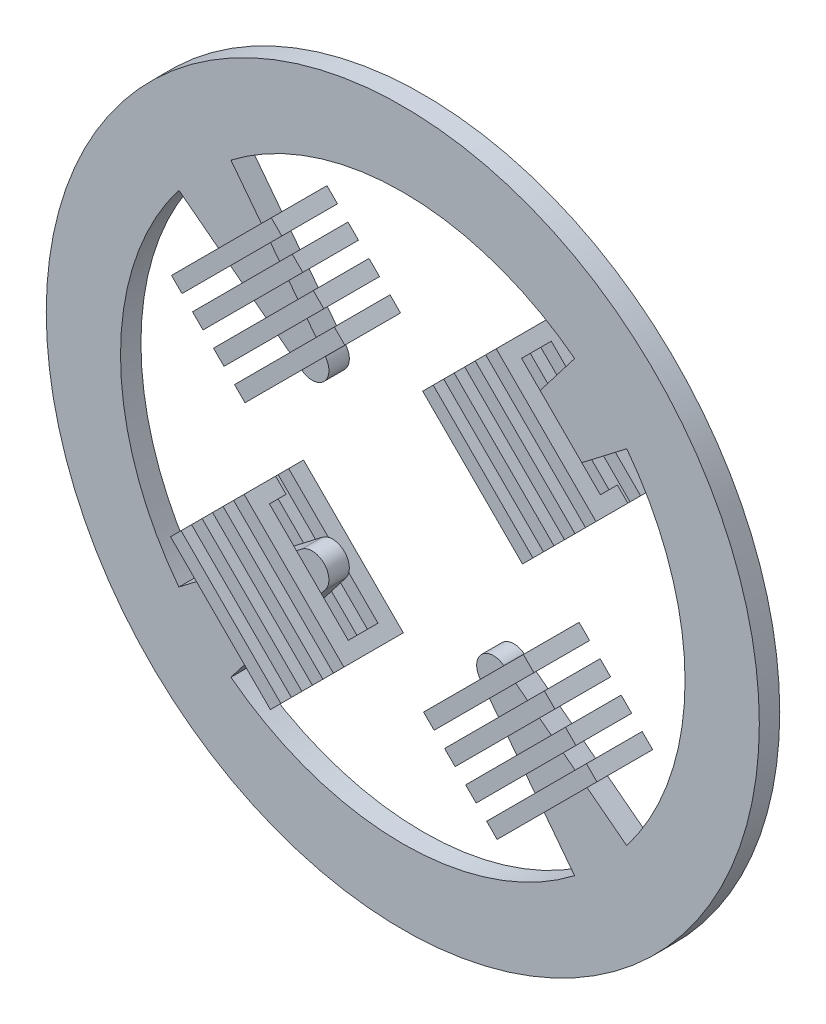
SolidWorks part; units mm, degrees
other "標示1"
sketch "草圖65"
ref_plane "前基準面" through (0, 0, 0) normal (0, 0, 1) x (1, 0, 0)
ref_plane "上基準面" through (0, 0, 0) normal (0, 1, 0) x (1, 0, 0)
ref_plane "右基準面" through (0, 0, 0) normal (1, 0, 0) x (0, 0, -1)
sketch "草圖1" plane through (0, 0, 0) normal (0, 0, 1) x (1, 0, 0)
  circle A0 centre (0, 0) radius 0.96
  circle A1 centre (0, 0) radius 0.76
extrude "填料-伸長1" add sketch "草圖1" along normal blind 0.055
sketch "草圖2" plane through (0, 0, 0.055) normal (0, 0, 1) x (1, 0, 0)
  line L0 (0, 0) -> (0, 1.565) construction
  line L1 (0, 0) -> (-1.8584, 0) construction
  line L2 (-0.0447, 0.3392) -> (-0.0992, 0.7535)
  line L3 (0.0447, 0.3392) -> (0.0992, 0.7535)
  line L4 (0.2714, 0.2082) -> (0.6029, 0.4627)
  line L5 (0.2082, 0.2714) -> (0.4627, 0.6029)
  line L6 (0.2082, -0.2714) -> (0.4627, -0.6029)
  line L7 (0.2714, -0.2082) -> (0.6029, -0.4627)
  line L8 (-0.2714, -0.2082) -> (-0.6029, -0.4627)
  line L9 (-0.2082, -0.2714) -> (-0.4627, -0.6029)
  line L10 (-0.2082, 0.2714) -> (-0.4627, 0.6029)
  line L11 (-0.2714, 0.2082) -> (-0.6029, 0.4627)
  circle A0 centre (0, 0) radius 0.3
  circle A1 centre (0, 0) radius 0.76 construction
  arc A3 (-0.0447, 0.3392) -> (0.0447, 0.3392) centre (0, 0.345) ccw
  arc A4 (0.0992, 0.7535) -> (-0.0992, 0.7535) centre (0, 0) ccw
  arc A5 (-0.76, 0) -> (0.76, 0) centre (0, 0) ccw
  arc A6 (0.6029, 0.4627) -> (0.4627, 0.6029) centre (0, 0) ccw
  arc A7 (0.2082, 0.2714) -> (0.2714, 0.2082) centre (0.244, 0.244) ccw
  arc A8 (0.4627, -0.6029) -> (0.6029, -0.4627) centre (0, 0) ccw
  arc A9 (0.2714, -0.2082) -> (0.2082, -0.2714) centre (0.244, -0.244) ccw
  arc A10 (-0.6029, -0.4627) -> (-0.4627, -0.6029) centre (0, 0) ccw
  arc A11 (-0.2082, -0.2714) -> (-0.2714, -0.2082) centre (-0.244, -0.244) ccw
  arc A12 (-0.4627, 0.6029) -> (-0.6029, 0.4627) centre (0, 0) ccw
  arc A13 (-0.2714, 0.2082) -> (-0.2082, 0.2714) centre (-0.244, 0.244) ccw
  point P23 (0, 0)
  point P34 (0, 0)
  point P41 (0, 0)
  circle M4 centre (0, 0) radius 0.76
  dimension "D1" = 7.5
  dimension "D3" = 2
  dimension "D4" = 4
  dimension "D2" = 7.5
extrude "填料-伸長2" add sketch "草圖2" against normal blind 0.055 contours L11 A13 L10 M4 | L5 A7 L4 M4 | L7 A9 L6 M4 | A11 L8 L9 M4
sketch "草圖7" plane through (0, 0, 0.055) normal (0, 0, 1) x (1, 0, 0)
  line L0 (0.2121, 0.2121) -> (0.2404, 0.2404) construction
  line L1 (0.2404, 0.2404) -> (0.2013, 0.2795) construction
  line L2 (0.2404, 0.2404) -> (0.5894, 0.5894) construction
  line L3 (0.0244, -0.0244) -> (-0.6648, 0.6648) construction
  line L4 (0.2404, -0.2404) -> (0.3328, -0.148)
  arc A0 (0.2082, 0.2714) -> (0.2714, 0.2082) centre (0.244, 0.244) ccw construction
  arc A1 (-0.2082, -0.2714) -> (-0.2714, -0.2082) centre (-0.244, -0.244) ccw construction
  arc A2 (-0.2714, 0.2082) -> (-0.2082, 0.2714) centre (-0.244, 0.244) ccw construction
  arc A3 (0.2714, -0.2082) -> (0.2082, -0.2714) centre (0.244, -0.244) ccw construction
  point P5 (0.297, 0.297)
  point P7 (-0.2121, -0.2121)
  point P8 (0.3536, 0.3536)
  point P9 (0.4101, 0.4101)
  point P12 (-0.2404, -0.2404)
  point P16 (-0.297, -0.297)
  point P17 (-0.3536, -0.3536)
  point P18 (-0.4101, -0.4101)
  point P20 (0.2404, -0.2404)
  point P23 (-0.2404, 0.2404)
  point P24 (-0.2121, 0.2121)
  point P25 (0.2121, -0.2121)
  point P29 (0.297, -0.297)
  point P33 (0.3536, -0.3536)
  point P34 (0.4101, -0.4101)
  point P35 (-0.297, 0.297)
  point P36 (-0.3536, 0.3536)
  point P37 (-0.4101, 0.4101)
  point P40 (0.4667, -0.4667)
  point P41 (0.5233, -0.5233)
  point P42 (0.4667, 0.4667)
  point P43 (0.5233, 0.5233)
  point P44 (-0.4667, 0.4667)
  point P45 (-0.5233, 0.5233)
  point P46 (-0.4667, -0.4667)
  point P47 (-0.5233, -0.5233)
  point P48 (0, 0)
  dimension "D1" = 0.08
  dimension "D2" = 0.08
  dimension "D3" = 0.08
  dimension "D4" = 0.04
  dimension "D5" = 0.04
  dimension "D6" = 0.08
  dimension "D7" = 0.08
  dimension "D8" = 0.08
  dimension "D9" = 0.04
  dimension "D10" = 0.04
  dimension "D11" = 0.08
  dimension "D12" = 0.08
  dimension "D13" = 0.08
  dimension "D14" = 0.08
  dimension "D15" = 0.08
  dimension "D16" = 0.08
  dimension "D17" = 0.08
  dimension "D18" = 0.08
  dimension "D19" = 0.08
  dimension "D20" = 0.08
  dimension "D21" = 0.08
  dimension "D22" = 0.08
  dimension "D23" = 0.08
  dimension "D24" = 0.08
ref_plane "平面5" through (0.2404, 0.2404, 0) normal (0.7071, 0.7071, 0) x (-0.7071, 0.7071, 0)
sketch "草圖11" plane through (0.2404, 0.2404, 0) normal (0.7071, 0.7071, 0) x (-0.7071, 0.7071, 0)
  line L0 (0, 0.055) -> (0, 0.1261) construction
  line L1 (-0.15, 0.0675) -> (0.15, 0.0675)
  line L2 (0.19, 0.1075) -> (-0.19, 0.1075)
  line L7 (-0.19, -0.0525) -> (0.19, -0.0525)
  line L17 (0.19, 0.1075) -> (0.19, -0.0525)
  line L18 (-0.19, 0.1075) -> (-0.19, -0.0525)
  line L19 (-0.15, -0.0125) -> (0.15, -0.0125)
  line L20 (-0.15, 0.0675) -> (-0.15, -0.0125)
  line L21 (0.15, 0.0675) -> (0.15, -0.0125)
  point P1 (0, 0.0275)
  point P2 (0, -0.0125)
  point P9 (0, 0.055)
  point P10 (0, -0.0525)
  point P11 (0, 0)
  point P13 (0, 0.1075)
  point P16 (0, -0.0525)
  point P19 (0, 0.0675)
  point P21 (0, 0.0675)
  point P22 (0, 0.1075)
  point P24 (0, -0.0125)
  dimension "D1" = 0.04
  dimension "D2" = 0.04
  dimension "D3" = 0.38
  dimension "D4" = 0.04
  dimension "D7" = 0.04
extrude "填料-伸長3" add sketch "草圖11" along normal blind 0.04 separate body
ref_plane "平面6" through (0.297, 0.297, 0) normal (0.7071, 0.7071, 0) x (0.7071, -0.7071, 0)
ref_plane "平面7" through (0.3536, 0.3536, 0) normal (0.7071, 0.7071, 0) x (0.7071, -0.7071, 0)
ref_plane "平面8" through (0.4101, 0.4101, 0) normal (0.7071, 0.7071, 0) x (0.7071, -0.7071, 0)
ref_plane "平面9" through (-0.2404, -0.2404, 0) normal (0.7071, 0.7071, 0) x (0.7071, -0.7071, 0)
ref_plane "平面10" through (-0.297, -0.297, 0) normal (0.7071, 0.7071, 0) x (0.7071, -0.7071, 0)
ref_plane "平面11" through (-0.3536, -0.3536, 0) normal (0.7071, 0.7071, 0) x (0.7071, -0.7071, 0)
ref_plane "平面12" through (-0.4101, -0.4101, 0) normal (0.7071, 0.7071, 0) x (0.7071, -0.7071, 0)
ref_plane "平面13" through (0.2404, -0.2404, 0) normal (0.7071, -0.7071, 0) x (0.7071, 0.7071, 0)
ref_plane "平面14" through (0.297, -0.297, 0) normal (0.7071, -0.7071, 0) x (0, 0, -1)
ref_plane "平面15" through (0.3536, -0.3536, 0) normal (0.7071, -0.7071, 0) x (0, 0, -1)
ref_plane "平面16" through (0.4101, -0.4101, 0) normal (0.7071, -0.7071, 0) x (0, 0, -1)
ref_plane "平面17" through (-0.2404, 0.2404, 0) normal (0.7071, -0.7071, 0) x (0, 0, -1)
ref_plane "平面18" through (-0.297, 0.297, 0) normal (0.7071, -0.7071, 0) x (0, 0, -1)
ref_plane "平面19" through (-0.3536, 0.3536, 0) normal (0.7071, -0.7071, 0) x (0, 0, -1)
ref_plane "平面20" through (-0.4101, 0.4101, 0) normal (0.7071, -0.7071, 0) x (0, 0, -1)
sketch "草圖60" plane through (0.2404, -0.2404, 0) normal (0.7071, -0.7071, 0) x (0.7071, 0.7071, 0)
sketch "草圖62" plane through (0.2404, -0.2404, 0) normal (0.7071, -0.7071, 0) x (0.7071, 0.7071, 0)
  line L0 (0, -0.0586) -> (0, 0.1686)
  line L2 (0.15, 0.065) -> (-0.15, 0.065)
  line L3 (-0.15, 0.065) -> (-0.15, -0.005)
  line L4 (-0.15, -0.005) -> (0.15, -0.005)
  line L5 (0.15, -0.005) -> (0.15, 0.065)
  line L6 (0.19, 0.105) -> (-0.19, 0.105)
  line L7 (-0.19, 0.105) -> (-0.19, -0.045)
  line L8 (-0.19, -0.045) -> (0.19, -0.045)
  line L9 (0.19, -0.045) -> (0.19, 0.105)
  point P0 (0, 0.065)
  point P4 (0, 0.055)
  point P5 (0, -0.005)
  point P8 (0, 0.105)
  point P11 (0, 0.065)
  point P14 (0, -0.045)
  point P18 (0, 0.105)
  dimension "D1" = 0.01
  dimension "D2" = 0.06
  dimension "D3" = 0.04
  dimension "D4" = 0.04
  dimension "D5" = 0.38
  dimension "D6" = 0.3
sketch "草圖64" plane through (0.297, -0.297, 0) normal (0.7071, -0.7071, 0) x (0, 0, -1)
  line L0 (0.045, 0.19) -> (-0.105, 0.19) construction
  line L1 (0.005, 0.15) -> (-0.065, 0.15) construction
  line L2 (0.045, -0.19) -> (0.045, 0.19) construction
  line L3 (0.005, -0.15) -> (0.005, 0.15) construction
  line L4 (-0.065, -0.15) -> (0.005, -0.15) construction
  line L5 (-0.065, 0.15) -> (-0.065, -0.15) construction
  line L6 (-0.105, -0.19) -> (0.045, -0.19) construction
  line L7 (-0.105, 0.19) -> (-0.105, -0.19) construction
  line L8 (0.045, 0.19) -> (-0.105, 0.19)
  line L9 (0.005, 0.15) -> (-0.065, 0.15)
  line L10 (0.045, -0.19) -> (0.045, 0.19)
  line L11 (0.005, -0.15) -> (0.005, 0.15)
  line L12 (-0.065, -0.15) -> (0.005, -0.15)
  line L13 (-0.065, 0.15) -> (-0.065, -0.15)
  line L14 (-0.105, -0.19) -> (0.045, -0.19)
  line L15 (-0.105, 0.19) -> (-0.105, -0.19)
sketch "草圖68" plane through (0.3536, -0.3536, 0) normal (0.7071, -0.7071, 0) x (0, 0, -1)
  line L0 (-0.105, -0.19) -> (0.045, -0.19) construction
  line L1 (-0.065, -0.15) -> (0.005, -0.15) construction
  line L2 (0.005, -0.15) -> (0.005, 0.15) construction
  line L3 (-0.065, 0.15) -> (-0.065, -0.15) construction
  line L4 (0.005, 0.15) -> (-0.065, 0.15) construction
  line L5 (0.045, -0.19) -> (0.045, 0.19) construction
  line L6 (0.045, 0.19) -> (-0.105, 0.19) construction
  line L7 (-0.105, 0.19) -> (-0.105, -0.19) construction
  line L8 (-0.105, -0.19) -> (0.045, -0.19)
  line L9 (-0.065, -0.15) -> (0.005, -0.15)
  line L10 (0.005, -0.15) -> (0.005, 0.15)
  line L11 (-0.065, 0.15) -> (-0.065, -0.15)
  line L12 (0.005, 0.15) -> (-0.065, 0.15)
  line L13 (0.045, -0.19) -> (0.045, 0.19)
  line L14 (0.045, 0.19) -> (-0.105, 0.19)
  line L15 (-0.105, 0.19) -> (-0.105, -0.19)
sketch "草圖69" plane through (0.4101, -0.4101, 0) normal (0.7071, -0.7071, 0) x (0, 0, -1)
  line L0 (0.045, -0.19) -> (0.045, 0.19) construction
  line L1 (0.045, 0.19) -> (-0.105, 0.19) construction
  line L2 (-0.105, 0.19) -> (-0.105, -0.19) construction
  line L3 (-0.105, -0.19) -> (0.045, -0.19) construction
  line L4 (-0.065, -0.15) -> (0.005, -0.15) construction
  line L5 (0.005, -0.15) -> (0.005, 0.15) construction
  line L6 (-0.065, 0.15) -> (-0.065, -0.15) construction
  line L7 (0.005, 0.15) -> (-0.065, 0.15) construction
  line L8 (0.045, -0.19) -> (0.045, 0.19)
  line L9 (0.045, 0.19) -> (-0.105, 0.19)
  line L10 (-0.105, 0.19) -> (-0.105, -0.19)
  line L11 (-0.105, -0.19) -> (0.045, -0.19)
  line L12 (-0.065, -0.15) -> (0.005, -0.15)
  line L13 (0.005, -0.15) -> (0.005, 0.15)
  line L14 (-0.065, 0.15) -> (-0.065, -0.15)
  line L15 (0.005, 0.15) -> (-0.065, 0.15)
sketch "草圖70" plane through (-0.2404, 0.2404, 0) normal (0.7071, -0.7071, 0) x (0, 0, -1)
  line L0 (-0.105, 0.19) -> (-0.105, -0.19) construction
  line L1 (-0.105, -0.19) -> (0.045, -0.19) construction
  line L2 (-0.065, -0.15) -> (0.005, -0.15) construction
  line L3 (-0.065, 0.15) -> (-0.065, -0.15) construction
  line L4 (0.005, -0.15) -> (0.005, 0.15) construction
  line L5 (0.005, 0.15) -> (-0.065, 0.15) construction
  line L6 (0.045, -0.19) -> (0.045, 0.19) construction
  line L7 (0.045, 0.19) -> (-0.105, 0.19) construction
  line L8 (-0.105, 0.19) -> (-0.105, -0.19)
  line L9 (-0.105, -0.19) -> (0.045, -0.19)
  line L10 (-0.065, -0.15) -> (0.005, -0.15)
  line L11 (-0.065, 0.15) -> (-0.065, -0.15)
  line L12 (0.005, -0.15) -> (0.005, 0.15)
  line L13 (0.005, 0.15) -> (-0.065, 0.15)
  line L14 (0.045, -0.19) -> (0.045, 0.19)
  line L15 (0.045, 0.19) -> (-0.105, 0.19)
sketch "草圖71" plane through (-0.297, 0.297, 0) normal (0.7071, -0.7071, 0) x (0, 0, -1)
  line L0 (0.045, -0.19) -> (0.045, 0.19) construction
  line L1 (-0.105, -0.19) -> (0.045, -0.19) construction
  line L2 (-0.065, -0.15) -> (0.005, -0.15) construction
  line L3 (0.005, -0.15) -> (0.005, 0.15) construction
  line L4 (-0.065, 0.15) -> (-0.065, -0.15) construction
  line L5 (0.005, 0.15) -> (-0.065, 0.15) construction
  line L6 (-0.105, 0.19) -> (-0.105, -0.19) construction
  line L7 (0.045, 0.19) -> (-0.105, 0.19) construction
  line L8 (0.045, -0.19) -> (0.045, 0.19)
  line L9 (-0.105, -0.19) -> (0.045, -0.19)
  line L10 (-0.065, -0.15) -> (0.005, -0.15)
  line L11 (0.005, -0.15) -> (0.005, 0.15)
  line L12 (-0.065, 0.15) -> (-0.065, -0.15)
  line L13 (0.005, 0.15) -> (-0.065, 0.15)
  line L14 (-0.105, 0.19) -> (-0.105, -0.19)
  line L15 (0.045, 0.19) -> (-0.105, 0.19)
sketch "草圖72" plane through (-0.3536, 0.3536, 0) normal (0.7071, -0.7071, 0) x (0, 0, -1)
  line L0 (-0.105, -0.19) -> (0.045, -0.19) construction
  line L1 (-0.105, 0.19) -> (-0.105, -0.19) construction
  line L2 (-0.065, 0.15) -> (-0.065, -0.15) construction
  line L3 (0.005, -0.15) -> (0.005, 0.15) construction
  line L4 (0.005, 0.15) -> (-0.065, 0.15) construction
  line L5 (0.045, 0.19) -> (-0.105, 0.19) construction
  line L6 (0.045, -0.19) -> (0.045, 0.19) construction
  line L7 (-0.105, -0.19) -> (0.045, -0.19)
  line L8 (-0.105, 0.19) -> (-0.105, -0.19)
  line L9 (-0.065, 0.15) -> (-0.065, -0.15)
  line L10 (0.005, -0.15) -> (0.005, 0.15)
  line L11 (0.005, 0.15) -> (-0.065, 0.15)
  line L12 (0.045, 0.19) -> (-0.105, 0.19)
  line L13 (0.045, -0.19) -> (0.045, 0.19)
  line L14 (-0.065, -0.15) -> (0.005, -0.15)
sketch "草圖73" plane through (-0.4101, 0.4101, 0) normal (0.7071, -0.7071, 0) x (0, 0, -1)
  line L0 (-0.065, -0.15) -> (0.005, -0.15) construction
  line L1 (-0.105, -0.19) -> (0.045, -0.19) construction
  line L2 (-0.105, 0.19) -> (-0.105, -0.19) construction
  line L3 (-0.065, 0.15) -> (-0.065, -0.15) construction
  line L4 (0.005, 0.15) -> (-0.065, 0.15) construction
  line L5 (0.005, -0.15) -> (0.005, 0.15) construction
  line L6 (0.045, -0.19) -> (0.045, 0.19) construction
  line L7 (0.045, 0.19) -> (-0.105, 0.19) construction
  line L8 (-0.065, -0.15) -> (0.005, -0.15)
  line L9 (-0.105, -0.19) -> (0.045, -0.19)
  line L10 (-0.105, 0.19) -> (-0.105, -0.19)
  line L11 (-0.065, 0.15) -> (-0.065, -0.15)
  line L12 (0.005, 0.15) -> (-0.065, 0.15)
  line L13 (0.005, -0.15) -> (0.005, 0.15)
  line L14 (0.045, -0.19) -> (0.045, 0.19)
  line L15 (0.045, 0.19) -> (-0.105, 0.19)
sketch "草圖74" plane through (-0.3536, 0.3536, 0) normal (0.7071, -0.7071, 0) x (0, 0, -1)
  line L0 (-0.065, -0.15) -> (0.005, -0.15) construction
  line L1 (-0.065, -0.15) -> (0.005, -0.15)
extrude "填料-伸長28" add sketch "草圖62" along normal blind 0.04 separate body contours L8 L9 L6 L0 L2 L5 L4 | L7 L8 L0 L4 L3 L2 L6
extrude "填料-伸長29" add sketch "草圖64" along normal blind 0.04 separate body
extrude "填料-伸長30" add sketch "草圖68" along normal blind 0.04 separate body
extrude "填料-伸長31" add sketch "草圖69" along normal blind 0.04 separate body
extrude "填料-伸長32" add sketch "草圖70" against normal blind 0.04 separate body
extrude "填料-伸長33" add sketch "草圖71" against normal blind 0.04 separate body
extrude "填料-伸長34" add sketch "草圖72" against normal blind 0.04 separate body
extrude "填料-伸長35" add sketch "草圖73" against normal blind 0.04 separate body
sketch "草圖76" plane through (0.297, 0.297, 0) normal (0.7071, 0.7071, 0) x (0.7071, -0.7071, 0)
  line L0 (0.19, -0.1075) -> (0.19, 0.0525) construction
  line L1 (0.15, -0.0675) -> (0.15, 0.0125) construction
  line L2 (-0.19, -0.1075) -> (0.19, -0.1075) construction
  line L3 (0.15, -0.0675) -> (-0.15, -0.0675) construction
  line L4 (-0.15, -0.0675) -> (-0.15, 0.0125) construction
  line L5 (-0.19, -0.1075) -> (-0.19, 0.0525) construction
  line L6 (0.19, 0.0525) -> (-0.19, 0.0525) construction
  line L7 (0.15, 0.0125) -> (-0.15, 0.0125) construction
  line L8 (0.19, -0.1075) -> (0.19, 0.0525)
  line L9 (0.15, -0.0675) -> (0.15, 0.0125)
  line L10 (-0.19, -0.1075) -> (0.19, -0.1075)
  line L11 (0.15, -0.0675) -> (-0.15, -0.0675)
  line L12 (-0.15, -0.0675) -> (-0.15, 0.0125)
  line L13 (-0.19, -0.1075) -> (-0.19, 0.0525)
  line L14 (0.19, 0.0525) -> (-0.19, 0.0525)
  line L15 (0.15, 0.0125) -> (-0.15, 0.0125)
sketch "草圖77" plane through (0.3536, 0.3536, 0) normal (0.7071, 0.7071, 0) x (0.7071, -0.7071, 0)
  line L0 (0.19, -0.1075) -> (0.19, 0.0525) construction
  line L1 (0.15, -0.0675) -> (0.15, 0.0125) construction
  line L2 (-0.19, -0.1075) -> (0.19, -0.1075) construction
  line L3 (0.15, -0.0675) -> (-0.15, -0.0675) construction
  line L4 (-0.15, -0.0675) -> (-0.15, 0.0125) construction
  line L5 (-0.19, -0.1075) -> (-0.19, 0.0525) construction
  line L6 (0.19, 0.0525) -> (-0.19, 0.0525) construction
  line L7 (0.15, 0.0125) -> (-0.15, 0.0125) construction
  line L8 (0.19, -0.1075) -> (0.19, 0.0525)
  line L9 (0.15, -0.0675) -> (0.15, 0.0125)
  line L10 (-0.19, -0.1075) -> (0.19, -0.1075)
  line L11 (0.15, -0.0675) -> (-0.15, -0.0675)
  line L12 (-0.15, -0.0675) -> (-0.15, 0.0125)
  line L13 (-0.19, -0.1075) -> (-0.19, 0.0525)
  line L14 (0.19, 0.0525) -> (-0.19, 0.0525)
  line L15 (0.15, 0.0125) -> (-0.15, 0.0125)
sketch "草圖78" plane through (0.4101, 0.4101, 0) normal (0.7071, 0.7071, 0) x (0.7071, -0.7071, 0)
  line L0 (0.19, -0.1075) -> (0.19, 0.0525) construction
  line L1 (-0.19, -0.1075) -> (0.19, -0.1075) construction
  line L2 (0.19, 0.0525) -> (-0.19, 0.0525) construction
  line L3 (-0.19, -0.1075) -> (-0.19, 0.0525) construction
  line L4 (0.15, -0.0675) -> (-0.15, -0.0675) construction
  line L5 (0.15, -0.0675) -> (0.15, 0.0125) construction
  line L6 (0.15, 0.0125) -> (-0.15, 0.0125) construction
  line L7 (-0.15, -0.0675) -> (-0.15, 0.0125) construction
  line L8 (0.19, -0.1075) -> (0.19, 0.0525)
  line L9 (-0.19, -0.1075) -> (0.19, -0.1075)
  line L10 (0.19, 0.0525) -> (-0.19, 0.0525)
  line L11 (-0.19, -0.1075) -> (-0.19, 0.0525)
  line L12 (0.15, -0.0675) -> (-0.15, -0.0675)
  line L13 (0.15, -0.0675) -> (0.15, 0.0125)
  line L14 (0.15, 0.0125) -> (-0.15, 0.0125)
  line L15 (-0.15, -0.0675) -> (-0.15, 0.0125)
sketch "草圖79" plane through (-0.2404, -0.2404, 0) normal (0.7071, 0.7071, 0) x (0.7071, -0.7071, 0)
  line L0 (-0.19, -0.1075) -> (0.19, -0.1075) construction
  line L1 (0.15, -0.0675) -> (-0.15, -0.0675) construction
  line L2 (-0.15, -0.0675) -> (-0.15, 0.0125) construction
  line L3 (-0.19, -0.1075) -> (-0.19, 0.0525) construction
  line L4 (0.19, -0.1075) -> (0.19, 0.0525) construction
  line L5 (0.15, -0.0675) -> (0.15, 0.0125) construction
  line L6 (0.15, 0.0125) -> (-0.15, 0.0125) construction
  line L7 (0.19, 0.0525) -> (-0.19, 0.0525) construction
  line L8 (-0.19, -0.1075) -> (0.19, -0.1075)
  line L9 (0.15, -0.0675) -> (-0.15, -0.0675)
  line L10 (-0.15, -0.0675) -> (-0.15, 0.0125)
  line L11 (-0.19, -0.1075) -> (-0.19, 0.0525)
  line L12 (0.19, -0.1075) -> (0.19, 0.0525)
  line L13 (0.15, -0.0675) -> (0.15, 0.0125)
  line L14 (0.15, 0.0125) -> (-0.15, 0.0125)
  line L15 (0.19, 0.0525) -> (-0.19, 0.0525)
sketch "草圖80" plane through (-0.297, -0.297, 0) normal (0.7071, 0.7071, 0) x (0.7071, -0.7071, 0)
  line L0 (-0.19, -0.1075) -> (0.19, -0.1075) construction
  line L1 (0.19, -0.1075) -> (0.19, 0.0525) construction
  line L2 (0.19, 0.0525) -> (-0.19, 0.0525) construction
  line L3 (-0.19, -0.1075) -> (-0.19, 0.0525) construction
  line L4 (-0.15, -0.0675) -> (-0.15, 0.0125) construction
  line L5 (0.15, -0.0675) -> (-0.15, -0.0675) construction
  line L6 (0.15, -0.0675) -> (0.15, 0.0125) construction
  line L7 (0.15, 0.0125) -> (-0.15, 0.0125) construction
  line L8 (-0.19, -0.1075) -> (0.19, -0.1075)
  line L9 (0.19, -0.1075) -> (0.19, 0.0525)
  line L10 (0.19, 0.0525) -> (-0.19, 0.0525)
  line L11 (-0.19, -0.1075) -> (-0.19, 0.0525)
  line L12 (-0.15, -0.0675) -> (-0.15, 0.0125)
  line L13 (0.15, -0.0675) -> (-0.15, -0.0675)
  line L14 (0.15, -0.0675) -> (0.15, 0.0125)
  line L15 (0.15, 0.0125) -> (-0.15, 0.0125)
sketch "草圖81" plane through (-0.3536, -0.3536, 0) normal (0.7071, 0.7071, 0) x (0.7071, -0.7071, 0)
  line L0 (-0.19, -0.1075) -> (0.19, -0.1075) construction
  line L1 (0.19, -0.1075) -> (0.19, 0.0525) construction
  line L2 (0.19, 0.0525) -> (-0.19, 0.0525) construction
  line L3 (-0.19, -0.1075) -> (-0.19, 0.0525) construction
  line L4 (-0.15, -0.0675) -> (-0.15, 0.0125) construction
  line L5 (0.15, -0.0675) -> (-0.15, -0.0675) construction
  line L6 (0.15, -0.0675) -> (0.15, 0.0125) construction
  line L7 (0.15, 0.0125) -> (-0.15, 0.0125) construction
  line L8 (-0.19, -0.1075) -> (0.19, -0.1075)
  line L9 (0.19, -0.1075) -> (0.19, 0.0525)
  line L10 (0.19, 0.0525) -> (-0.19, 0.0525)
  line L11 (-0.19, -0.1075) -> (-0.19, 0.0525)
  line L12 (-0.15, -0.0675) -> (-0.15, 0.0125)
  line L13 (0.15, -0.0675) -> (-0.15, -0.0675)
  line L14 (0.15, -0.0675) -> (0.15, 0.0125)
  line L15 (0.15, 0.0125) -> (-0.15, 0.0125)
sketch "草圖82" plane through (-0.4101, -0.4101, 0) normal (0.7071, 0.7071, 0) x (0.7071, -0.7071, 0)
  line L0 (0.19, -0.1075) -> (0.19, 0.0525) construction
  line L1 (-0.19, -0.1075) -> (0.19, -0.1075) construction
  line L2 (-0.15, -0.0675) -> (-0.15, 0.0125) construction
  line L3 (0.15, -0.0675) -> (-0.15, -0.0675) construction
  line L4 (0.15, -0.0675) -> (0.15, 0.0125) construction
  line L5 (0.15, 0.0125) -> (-0.15, 0.0125) construction
  line L6 (0.19, 0.0525) -> (-0.19, 0.0525) construction
  line L7 (-0.19, -0.1075) -> (-0.19, 0.0525) construction
  line L8 (0.19, -0.1075) -> (0.19, 0.0525)
  line L9 (-0.19, -0.1075) -> (0.19, -0.1075)
  line L10 (-0.15, -0.0675) -> (-0.15, 0.0125)
  line L11 (0.15, -0.0675) -> (-0.15, -0.0675)
  line L12 (0.15, -0.0675) -> (0.15, 0.0125)
  line L13 (0.15, 0.0125) -> (-0.15, 0.0125)
  line L14 (0.19, 0.0525) -> (-0.19, 0.0525)
  line L15 (-0.19, -0.1075) -> (-0.19, 0.0525)
extrude "填料-伸長36" add sketch "草圖76" along normal blind 0.04 separate body
extrude "填料-伸長37" add sketch "草圖77" along normal blind 0.04 separate body
extrude "填料-伸長38" add sketch "草圖78" along normal blind 0.04 separate body
extrude "填料-伸長39" add sketch "草圖79" against normal blind 0.04 separate body
extrude "填料-伸長40" add sketch "草圖80" against normal blind 0.04 separate body
extrude "填料-伸長41" add sketch "草圖81" against normal blind 0.04 separate body
extrude "填料-伸長42" add sketch "草圖82" against normal blind 0.04 separate body
sketch "草圖84" plane through (0.4384, 0.4384, 0) normal (0.7071, 0.7071, 0) x (0, 0, -1)
  line L0 (0.0125, -0.15) -> (0.0125, -0.19)
  line L1 (-0.1075, -0.19) -> (0.0525, -0.19) construction
  line L2 (0.0125, -0.15) -> (-0.0218, -0.15)
  line L3 (-0.0675, -0.15) -> (0.0125, -0.15) construction
  line L4 (-0.0218, -0.15) -> (-0.0218, -0.19)
  line L5 (-0.0218, -0.19) -> (0.0125, -0.19)
extrude "除料-伸長2" cut sketch "草圖84" against normal blind 0.5
sketch "草圖85" plane through (-0.4384, -0.4384, 0) normal (-0.7071, -0.7071, 0) x (0, 0, 1)
  line L0 (-0.0125, 0.15) -> (-0.0125, 0.19)
  line L1 (-0.0525, 0.19) -> (0.1075, 0.19) construction
  line L2 (-0.0125, 0.19) -> (0.0228, 0.19)
  line L3 (0.0228, 0.19) -> (0.0228, 0.15)
  line L4 (-0.0125, 0.15) -> (0.0675, 0.15) construction
  line L5 (0.0228, 0.15) -> (-0.0125, 0.15)
extrude "除料-伸長3" cut sketch "草圖85" against normal blind 0.5
